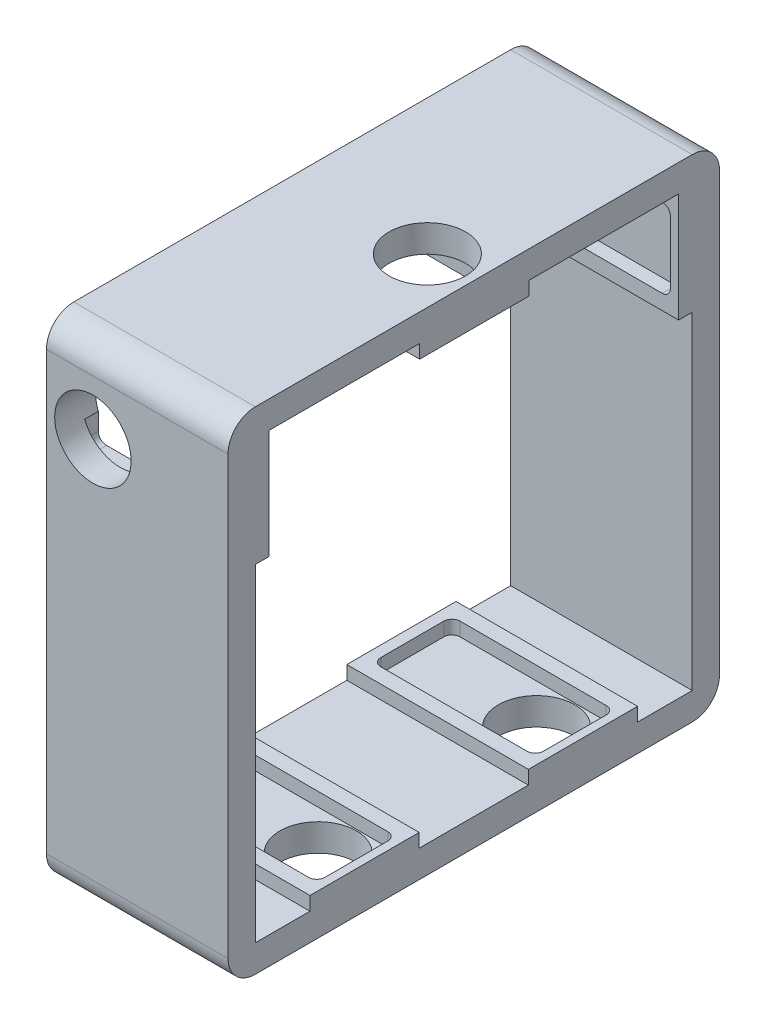
SolidWorks part; units mm, degrees
ref_plane "Front Plane" through (0, 0, 0) normal (0, 0, 1) x (1, 0, 0)
ref_plane "Top Plane" through (0, 0, 0) normal (0, 1, 0) x (1, 0, 0)
ref_plane "Right Plane" through (0, 0, 0) normal (1, 0, 0) x (0, 0, -1)
sketch "Sketch1" plane through (0, 0, 0) normal (0, 0, 1) x (1, 0, 0)
  line L1 (0, 0) -> (66.5, 0)
  line L2 (0, 0) -> (0, 180)
  line L3 (0, 180) -> (66.5, 180)
  line L4 (66.5, 0) -> (66.5, 180)
extrude "Boss-Extrude1" add sketch "Sketch1" along normal blind 180
sketch "Sketch3" plane through (0, 0, 0) normal (-1, 0, 0) x (0, 0, 1)
  line L9 (170, 10) -> (10, 10)
  line L10 (170, 10) -> (170, 170)
  line L11 (170, 170) -> (10, 170)
  line L12 (10, 10) -> (10, 170)
extrude "Cut-Extrude1" cut sketch "Sketch3" against normal blind 180
sketch "Sketch8" plane through (0, 0, 10) normal (0, 0, 1) x (1, 0, 0)
  line L0 (66.5, 170) -> (66.5, 10) construction
  line L1 (0, 170) -> (66.5, 170)
  line L2 (0, 170) -> (0, 130)
  line L3 (0, 130) -> (66.5, 130)
  line L4 (66.5, 170) -> (66.5, 130)
extrude "Boss-Extrude2" add sketch "Sketch8" along normal blind 5
sketch "Sketch10" plane through (0, 0, 170) normal (0, 0, -1) x (-1, 0, 0)
  line L0 (0, 10) -> (0, 170) construction
  line L1 (-66.5, 170) -> (0, 170)
  line L2 (-66.5, 170) -> (-66.5, 130)
  line L3 (-66.5, 130) -> (0, 130)
  line L4 (0, 170) -> (0, 130)
extrude "Boss-Extrude3" add sketch "Sketch10" along normal blind 5
sketch "Sketch5" plane through (0, 180, 0) normal (0, 1, 0) x (1, 0, 0)
  circle A1 centre (49.5, -90) radius 14
extrude "Cut-Extrude3" cut sketch "Sketch5" against normal blind 10
ref_plane "Plane4" through (0, 0, 0) normal (0, 0, -1) x (-1, 0, 0)
sketch "Sketch7" plane through (0, 0, 0) normal (0, -1, 0) x (1, 0, 0)
  circle A2 centre (49.5, 50) radius 14
  circle A3 centre (49.5, 130) radius 14
extrude "Cut-Extrude4" cut sketch "Sketch7" against normal blind 10
sketch "Sketch9" plane through (0, 0, 15) normal (0, 0, 1) x (1, 0, 0)
  line L5 (60.5, 164.5) -> (7.5, 164.5)
  line L12 (63.5, 161.5) -> (63.5, 138.5)
  line L13 (60.5, 135.5) -> (7.5, 135.5)
  line L14 (4.5, 161.5) -> (4.5, 138.5)
  arc A0 (7.5, 135.5) -> (4.5, 138.5) centre (7.5, 138.5) cw
  arc A5 (7.5, 164.5) -> (4.5, 161.5) centre (7.5, 161.5) ccw
  arc A6 (63.5, 161.5) -> (60.5, 164.5) centre (60.5, 161.5) ccw
  arc A7 (63.5, 138.5) -> (60.5, 135.5) centre (60.5, 138.5) cw
  point P3 (63.5, 150)
  dimension "D1" = 3
extrude "Cut-Extrude5" cut sketch "Sketch9" against normal blind 5
sketch "Sketch11" plane through (0, 0, 165) normal (0, 0, -1) x (-1, 0, 0)
  line L0 (-60.5, 164.5) -> (-7, 164.5)
  line L1 (-63.5, 161.5) -> (-63.5, 138.5)
  line L2 (-60.5, 135.5) -> (-7, 135.5)
  line L6 (-4, 161.5) -> (-4, 138.5)
  arc A1 (-7, 164.5) -> (-4, 161.5) centre (-7, 161.5) cw
  arc A2 (-7, 135.5) -> (-4, 138.5) centre (-7, 138.5) ccw
  arc A5 (-63.5, 138.5) -> (-60.5, 135.5) centre (-60.5, 138.5) ccw
  arc A6 (-60.5, 164.5) -> (-63.5, 161.5) centre (-60.5, 161.5) ccw
  point P8 (-57.5, 150)
  dimension "D1" = 3
  dimension "D2" = 3
extrude "Cut-Extrude6" cut sketch "Sketch11" against normal blind 5
sketch "Sketch12" plane through (0, 170, 0) normal (0, -1, 0) x (1, 0, 0)
  line L1 (66.5, 165) -> (66.5, 15) construction
  line L2 (66.5, 69.8335) -> (66.5, 109.8335)
  line L8 (66.5, 109.8335) -> (0, 109.8335)
  line L9 (66.5, 109.8335) -> (66.5, 69.8335)
  line L10 (66.5, 69.8335) -> (0, 69.8335)
  line L11 (0, 109.8335) -> (0, 69.8335)
  line L14 (60.5, 75.3335) -> (7, 75.3335)
  line L15 (63.5, 78.3335) -> (63.5, 101.3335)
  line L16 (60.5, 104.3335) -> (7, 104.3335)
  line L17 (4, 78.3335) -> (4, 101.3335)
  arc A0 (7, 104.3335) -> (4, 101.3335) centre (7, 101.3335) ccw
  arc A1 (63.5, 101.3335) -> (60.5, 104.3335) centre (60.5, 101.3335) ccw
  arc A2 (63.5, 78.3335) -> (60.5, 75.3335) centre (60.5, 78.3335) cw
  arc A3 (7, 75.3335) -> (4, 78.3335) centre (7, 78.3335) cw
  point P6 (63.5, 89.8335)
  point P7 (63.5, 89.8335)
  point P8 (57.5, 90)
  point P19 (57.5, 90)
  point P22 (66.5, 89.8335)
  dimension "D1" = 3
extrude "Boss-Extrude8" add sketch "Sketch12" along normal blind 5
sketch "Sketch15" plane through (0, 0, 0) normal (0, 0, -1) x (-1, 0, 0)
  circle A0 centre (-17, 150) radius 14
extrude "Cut-Extrude7" cut sketch "Sketch15" against normal blind 200
sketch "Sketch16" plane through (0, 10, 0) normal (0, 1, 0) x (1, 0, 0)
  line L1 (0, -10) -> (0, -170) construction
  line L2 (66.5, -10) -> (66.5, -170) construction
  line L4 (63.5, -38.5) -> (63.5, -61.5)
  line L5 (66.5, -30) -> (0, -30)
  line L6 (66.5, -70) -> (66.5, -30)
  line L7 (0, -30) -> (0, -70)
  line L8 (0, -70) -> (66.5, -70)
  line L9 (60.5, -35.5) -> (7, -35.5)
  line L10 (4, -38.5) -> (4, -61.5)
  line L11 (7, -64.5) -> (60.5, -64.5)
  line L20 (66.5, -110) -> (0, -110)
  line L21 (0, -110) -> (0, -150)
  line L22 (0, -150) -> (66.5, -150)
  line L23 (66.5, -150) -> (66.5, -110)
  line L26 (63.5, -141.5) -> (63.5, -118.5)
  line L27 (60.5, -115.5) -> (7, -115.5)
  line L28 (4, -118.5) -> (4, -141.5)
  line L29 (7, -144.5) -> (60.5, -144.5)
  arc A0 (4, -141.5) -> (7, -144.5) centre (7, -141.5) ccw
  arc A1 (63.5, -38.5) -> (60.5, -35.5) centre (60.5, -38.5) ccw
  arc A2 (7, -35.5) -> (4, -38.5) centre (7, -38.5) ccw
  arc A3 (63.5, -61.5) -> (60.5, -64.5) centre (60.5, -61.5) cw
  arc A4 (4, -61.5) -> (7, -64.5) centre (7, -61.5) ccw
  arc A9 (7, -115.5) -> (4, -118.5) centre (7, -118.5) ccw
  arc A10 (63.5, -118.5) -> (60.5, -115.5) centre (60.5, -118.5) ccw
  arc A11 (63.5, -141.5) -> (60.5, -144.5) centre (60.5, -141.5) cw
  point P16 (63.5, -50)
  dimension "D1" = 3
  dimension "D2" = 3
  dimension "D3" = 3
  dimension "D7" = 3
extrude "Boss-Extrude9" add sketch "Sketch16" along normal blind 5
fillet "Fillet1" radius 10 2 edges at (33.25, 180, 0) (33.25, 0, 0)
fillet "Fillet2" radius 10 2 edges at (33.25, 0, 180) (33.25, 180, 180)
